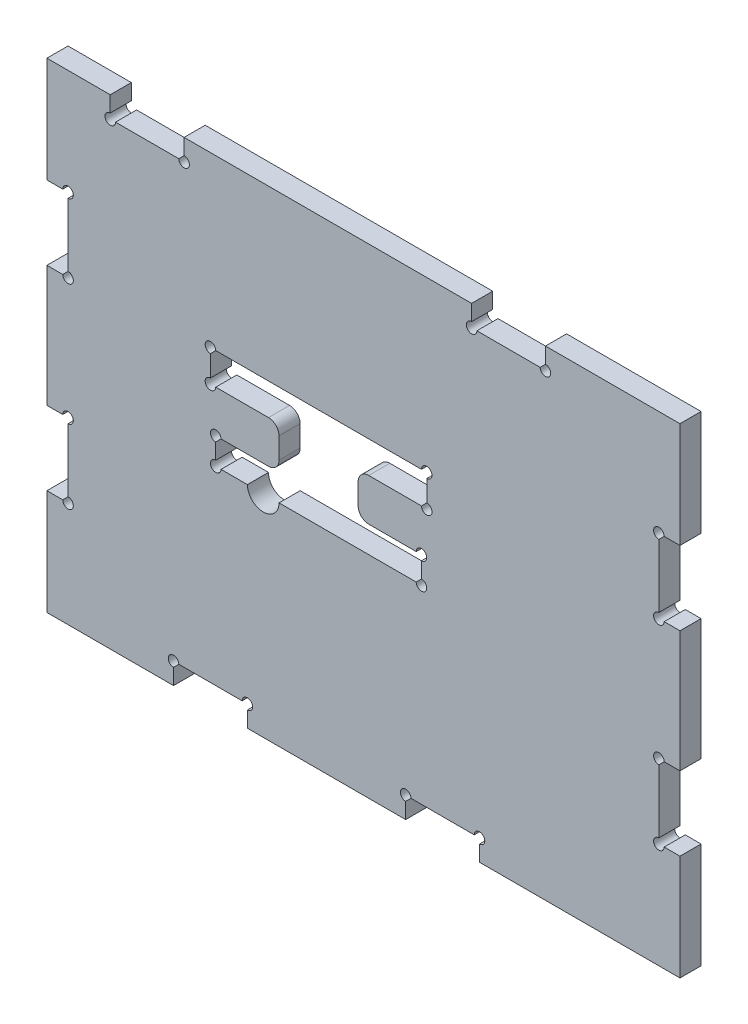
SolidWorks part; units mm, degrees
ref_plane "Front" through (0, 0, 0) normal (0, 0, 1) x (1, 0, 0)
ref_plane "Top" through (0, 0, 0) normal (0, 1, 0) x (1, 0, 0)
ref_plane "Right" through (0, 0, 0) normal (1, 0, 0) x (0, 0, -1)
sketch "草图1" plane through (0, 0, 0) normal (0, 0, 1) x (1, 0, 0)
  line L1 (0, 0) -> (60, 0)
  line L2 (0, 0) -> (0, 45.5)
  line L3 (0, 45.5) -> (60, 45.5)
  line L4 (60, 0) -> (60, 45.5)
  dimension "D1" = 60
  dimension "D2" = 45.5
extrude "凸台-拉伸1" add sketch "草图1" along normal blind 2
sketch "草图2" plane through (0, 0, 2) normal (0, 0, 1) x (1, 0, 0)
  line L0 (60, 45.5) -> (0, 45.5) construction
  line L1 (6, 45.5) -> (13, 45.5)
  line L2 (6, 45.5) -> (6, 43.5)
  line L3 (6, 43.5) -> (13, 43.5)
  line L4 (13, 45.5) -> (13, 43.5)
  line L5 (0, 45.5) -> (0, 0) construction
  line L6 (60, 0) -> (60, 45.5) construction
  line L7 (40.25, 45.5) -> (47.25, 45.5)
  line L8 (40.25, 45.5) -> (40.25, 43.5)
  line L9 (40.25, 43.5) -> (47.25, 43.5)
  line L10 (47.25, 45.5) -> (47.25, 43.5)
  line L11 (0, 0) -> (60, 0) construction
  line L12 (12, 0) -> (19, 0)
  line L13 (12, 0) -> (12, 2)
  line L14 (12, 2) -> (19, 2)
  line L15 (19, 0) -> (19, 2)
  line L17 (34, 0) -> (41, 0)
  line L18 (34, 0) -> (34, 2)
  line L19 (34, 2) -> (41, 2)
  line L20 (41, 0) -> (41, 2)
  line L21 (0, 35.5) -> (2, 35.5)
  line L22 (0, 35.5) -> (0, 28.5)
  line L23 (0, 28.5) -> (2, 28.5)
  line L24 (2, 35.5) -> (2, 28.5)
  line L25 (0, 17) -> (2, 17)
  line L26 (0, 17) -> (0, 10)
  line L27 (0, 10) -> (2, 10)
  line L28 (2, 17) -> (2, 10)
  line L29 (60, 35.5) -> (58, 35.5)
  line L30 (60, 35.5) -> (60, 28.5)
  line L31 (60, 28.5) -> (58, 28.5)
  line L32 (58, 35.5) -> (58, 28.5)
  line L33 (60, 17) -> (58, 17)
  line L34 (60, 17) -> (60, 10)
  line L35 (60, 10) -> (58, 10)
  line L36 (58, 17) -> (58, 10)
  dimension "D1" = 6
  dimension "D2" = 12.75
  dimension "D3" = 2
  dimension "D4" = 2
  dimension "D5" = 7
  dimension "D6" = 7
  dimension "D7" = 12
  dimension "D8" = 15
  dimension "D9" = 7
  dimension "D10" = 7
  dimension "D11" = 2
  dimension "D12" = 2
  dimension "D13" = 2
  dimension "D14" = 10
  dimension "D15" = 7
  dimension "D16" = 7
  dimension "D17" = 2
  dimension "D18" = 10
  dimension "D19" = 2
  dimension "D20" = 2
extrude "切除-拉伸1" cut sketch "草图2" against normal through all
sketch "草图3" plane through (0, 0, 2) normal (0, 0, 1) x (1, 0, 0)
  point P0 (6, 43.5)
  point P1 (13, 43.5)
  point P3 (40.25, 43.5)
  point P4 (47.25, 43.5)
  point P5 (12, 2)
  point P6 (19, 2)
  point P11 (34, 2)
  point P13 (41, 2)
  point P15 (2, 35.5)
  point P17 (2, 28.5)
  point P19 (2, 17)
  point P21 (2, 10)
  point P23 (58, 35.5)
  point P25 (58, 28.5)
  point P27 (58, 17)
  point P29 (58, 10)
sketch "草图4" plane through (0, 0, 2) normal (0, 0, 1) x (1, 0, 0)
  circle A0 centre (6, 43.5) radius 0.5
extrude "切除-拉伸2" cut sketch "草图4" against normal through all
sketch "草图5" plane through (0, 0, 2) normal (0, 0, 1) x (1, 0, 0)
  line L0 (40.25, 45.5) -> (13, 45.5) construction
  line L1 (15.5, 29.5) -> (36, 29.5)
  line L2 (15.5, 29.5) -> (15.5, 21.5)
  line L3 (15.5, 21.5) -> (36, 21.5)
  line L4 (36, 29.5) -> (36, 21.5)
  line L5 (0, 28.5) -> (0, 17) construction
  dimension "D1" = 16
  dimension "D2" = 15.5
  dimension "D3" = 20.5
  dimension "D4" = 8
extrude "切除-拉伸3" cut sketch "草图5" against normal through all
sketch "草图6" plane through (0, 0, 2) normal (0, 0, 1) x (1, 0, 0)
  line L0 (15.5, 29.5) -> (15.5, 21.5) construction
  line L1 (15.5, 26.5) -> (22, 26.5)
  line L2 (15.5, 26.5) -> (15.5, 21.5)
  line L3 (15.5, 21.5) -> (22, 21.5)
  line L4 (22, 26.5) -> (22, 21.5)
  line L5 (15.5, 21.5) -> (36, 21.5) construction
  line L6 (36, 21.5) -> (36, 29.5) construction
  line L7 (36, 26.5) -> (29.5, 26.5)
  line L8 (36, 26.5) -> (36, 21.5)
  line L9 (36, 21.5) -> (29.5, 21.5)
  line L10 (29.5, 26.5) -> (29.5, 21.5)
  line L11 (36, 29.5) -> (15.5, 29.5) construction
  dimension "D1" = 3
  dimension "D2" = 6.5
  dimension "D3" = 6.5
  dimension "D4" = 3
extrude "凸台-拉伸2" add sketch "草图6" against normal blind 2
sketch "草图7" plane through (0, 0, 2) normal (0, 0, 1) x (1, 0, 0)
  circle A0 centre (15.5, 29.5) radius 0.5
  circle A1 centre (15.5, 26.5) radius 0.5
  circle A2 centre (36, 29.5) radius 0.5
  circle A3 centre (36, 26.5) radius 0.5
extrude "切除-拉伸4" cut sketch "草图7" against normal through all
sketch "草图8" plane through (0, 0, 2) normal (0, 0, 1) x (1, 0, 0)
  line L0 (22, 21.5) -> (22, 26.5) construction
  line L1 (16, 22.5) -> (35.5, 22.5)
  line L2 (16, 22.5) -> (16, 20)
  line L3 (16, 20) -> (35.5, 20)
  line L4 (35.5, 22.5) -> (35.5, 20)
  line L5 (29.5, 26.5) -> (29.5, 21.5) construction
  line L6 (22, 26.5) -> (16, 26.5) construction
  dimension "D1" = 2.5
  dimension "D2" = 6
  dimension "D3" = 6
  dimension "D4" = 4
extrude "切除-拉伸5" cut sketch "草图8" against normal through all
fillet "圆角1" radius 1 4 edges at (29.5, 26.5, 1) (22, 26.5, 1) (29.5, 22.5, 1) (22, 22.5, 1)
pattern_sketch "草图阵列1" of "切除-拉伸2" driven by "草图3"
sketch "草图9" plane through (0, 0, 2) normal (0, 0, 1) x (1, 0, 0)
  circle A0 centre (16, 20) radius 0.5
  circle A1 centre (16, 22.5) radius 0.5
  circle A2 centre (35.5, 20) radius 0.5
  circle A3 centre (35.5, 22.5) radius 0.5
extrude "切除-拉伸6" cut sketch "草图9" against normal blind 2
sketch "草图10" plane through (0, 0, 2) normal (0, 0, 1) x (1, 0, 0)
  line L0 (16.5, 20) -> (35, 20) construction
  circle A0 centre (20.5, 20) radius 1.5
  arc A1 (16, 20.5) -> (16.5, 20) centre (16, 20) ccw construction
  dimension "D1" = 4.5
  dimension "D2" = 3
extrude "切除-拉伸7" cut sketch "草图10" against normal through all
